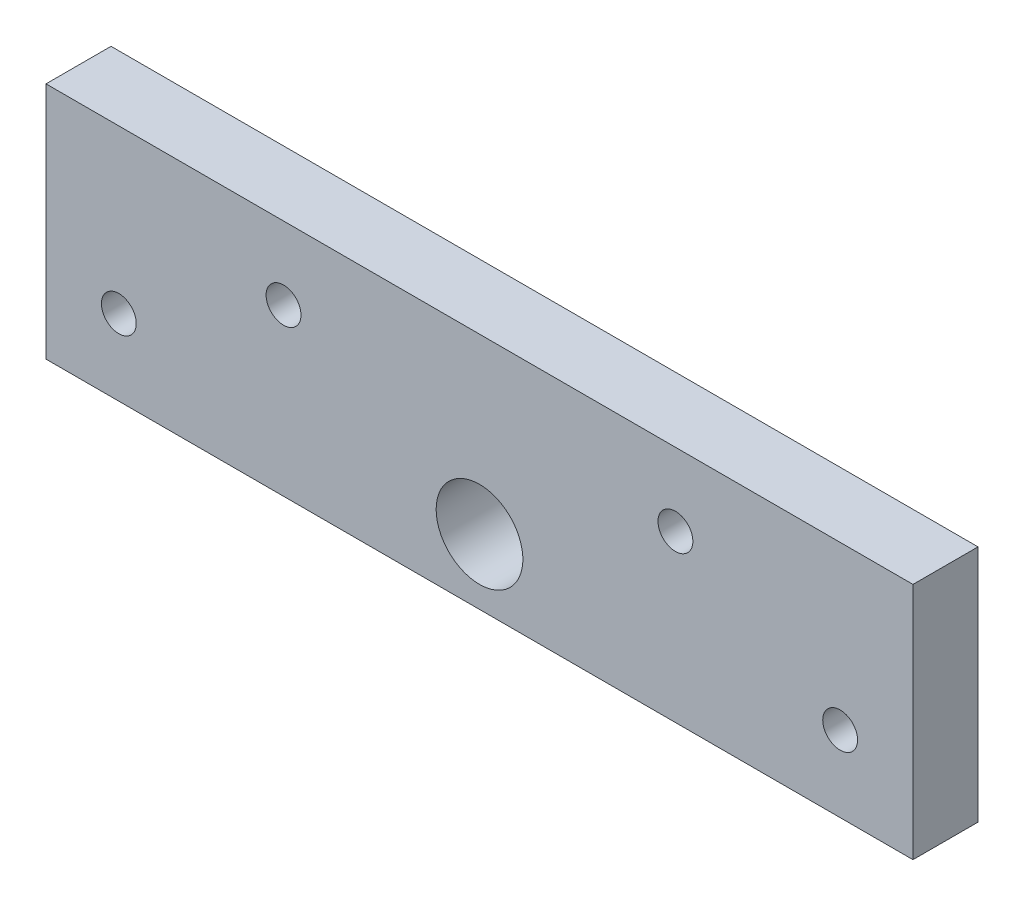
SolidWorks part; units mm, degrees
material "6061-T6 (SS)"
ref_plane "Front Plane" through (0, 0, 0) normal (0, 0, 1) x (1, 0, 0)
ref_plane "Top Plane" through (0, 0, 0) normal (0, 1, 0) x (1, 0, 0)
ref_plane "Right Plane" through (0, 0, 0) normal (1, 0, 0) x (0, 0, -1)
sketch "Sketch8" plane through (0, 0, 0) normal (0, 0, 1) x (1, 0, 0)
  point P0 (0, 0)
  line B0 (-63.5, -15.875) -> (63.5, -15.875)
  line B1 (63.5, -15.875) -> (63.5, 0)
  line B2 (36.5092, 0) -> (47.625, 15.875)
  line B3 (47.625, 15.875) -> (16.0563, 15.875)
  line B4 (-39.8731, 15.875) -> (-28.7573, 0)
  line B5 (-28.7573, 0) -> (-63.5, 0)
  line B6 (-36.5092, 0) -> (-47.625, 15.875)
  line B7 (-47.625, 15.875) -> (-39.8731, 15.875)
  line B8 (-16.0563, 15.875) -> (-16.0563, -3.175)
  line B9 (-16.0563, -3.175) -> (16.0563, -3.175)
  line B10 (16.0563, -3.175) -> (16.0563, 15.875)
  line B11 (-16.0563, 15.875) -> (-39.8731, 15.875)
  line B12 (-63.5, 0) -> (-63.5, 31.75)
  line B13 (-63.5, 31.75) -> (63.5, 31.75)
  line B14 (-16.0563, 15.875) -> (16.0563, 15.875)
  line B15 (0, 31.75) -> (0, -15.875) construction
  line B16 (-36.5092, 0) -> (36.5092, 0) construction
  line B17 (-28.702, 21.082) -> (28.702, 21.082) construction
  line B18 (-25.4, -8.001) -> (25.4, -8.001) construction
  line B19 (-25.4, -8.001) -> (-25.4, 7.9375) construction
  line B20 (-52.832, 7.9375) -> (52.832, 7.9375) construction
  circle B21 centre (0, 6.35) radius 18.669 construction
sketch_block_instance "dovetail pair-1"
sketch_block "Block1" parameters "D8"=37.338, "D1"=55, "D2"=127, "D3"=6.35, "D4"=15.875, "D5"=31.75, "D6"=95.25, "D7"=19.05, "D9"=55, "D10"=31.75, "D11"=50.8, "D12"=23.876, "D13"=7.874, "D14"=10.668, "D15"=34.798, "D16"=21.082, "D17"=7.9375
sketch "Sketch1" plane through (0, 0, 0) normal (0, 0, 1) x (1, 0, 0)
  line L0 (63.5, -15.875) -> (63.5, 0) construction
  line L1 (-63.5, 31.75) -> (63.5, 31.75)
  line L2 (-63.5, 31.75) -> (-63.5, -3.175)
  line L3 (-63.5, -3.175) -> (63.5, -3.175)
  line L4 (63.5, 31.75) -> (63.5, -3.175)
  line L5 (-16.0563, -3.175) -> (16.0563, -3.175) construction
  circle A0 centre (0, 6.35) radius 6.35
  dimension "D1" = 12.7
extrude "Boss-Extrude1" add sketch "Sketch1" along normal blind 9.525
hole_wizard "CBORE for #10 Socket Head Cap Screw1" positions "Sketch6" profile "Sketch7" counterbore size "#10" standard "ANSI Inch" end condition up to next
sketch "Sketch6" plane through (248.3324, -44.45, 0) normal (0, 0, -1) x (-1, 0, 0)
  point P26 (219.6304, 65.532)
  point P28 (195.5004, 52.3875)
  point P30 (277.0344, 65.532)
  point P32 (301.1644, 52.3875)
sketch "Sketch7" plane through (28.702, 21.082, 0) normal (1, 0, 0) x (0, 1, 0)
  line L0 (0, 0) -> (0, 9.525)
  line L1 (0, 9.525) -> (2.5527, 9.525)
  line L3 (2.5527, 9.525) -> (2.5527, 4.826)
  line L4 (4.7625, 4.826) -> (2.5527, 4.826)
  line L5 (4.7625, 4.826) -> (4.7625, 0.635)
  line L6 (4.7625, 0.635) -> (5.3975, 0)
  line L7 (5.3975, 0) -> (0, 0)
  line L8 (-4.7625, 0.635) -> (-5.3975, 0) construction
  line L11 (0, -6.35) -> (0, 107.95) construction
  dimension "Thru Hole Dia." = 5.1054
  dimension "Thru Hole Depth" = 9.525
  dimension "C'Bore Dia." = 9.525
  dimension "C'Bore Depth" = 4.826
  dimension "Near C'Sink Dia." = 10.795
  dimension "Near C'Sink Angle" = 90
equation "\"dovetail-angle\" = 55"
equation "\"dovetail-stock-width\" = 5"
equation "\"dovetail-stock-height\" = 1.25"
equation "\"dovetail-depth\" = 0.5 * \"dovetail-stock-height\""
equation "\"dovetail-throat-width\" = \"dovetail-stock-width\" - (2 * \"dovetail-depth\")"
equation "\"delta-x\" = 6"
equation "\"delta-y\" = 3"
equation "\"gib-thickness\" = 0.25"
equation "\"x-slide-length\" = \"dovetail-stock-width\" + \"delta-x\""
equation "\"y-slide-length\" = \"dovetail-stock-width\" + \"delta-y\""
equation "\"dog-point-diam\" = .149"
equation "\"dog-point-length\" = .067"
equation "\"dovetail-double-height\" = 2 * \"dovetail-depth\" + 0.5"
equation "\"acme-major-diam\" = .5"
equation "\"acme-pitch-diam\" = 0.45"
equation "\"acme-minor-diam\" = 0.4"
equation "\"x-screw-length\" = \"x-slide-length\" + \"screw-add-length\""
equation "\"y-screw-length\" = \"y-slide-length\" + \"screw-add-length\""
equation "\"acme-nut-od\" = 1.47"
equation "\"acme-nut-length\" = 1"
equation "\"acme-nut-trim-height\" = .75"
equation "\"D1@Sketch1\"=\"screw-bearing-od\""
equation "\"screw-bearing-od\" = 0.5"
equation "\"screw-bearing-length\" = .375"
equation "\"end-plate-thickness\" = \"screw-bearing-length\""
equation "\"D1@Boss-Extrude1\"=\"end-plate-thickness\""
equation "\"screw-bearing-id\" = .375"
equation "\"screw-add-length\" = 2 * \"end-plate-thickness\" + 1 + 0.5"
equation "\"acme-nut-mount-hole-space-horz\" = 0.95"
equation "\"acme-nut-mount-hole-space-vert\" = 0.5 * \"acme-nut-length\""
